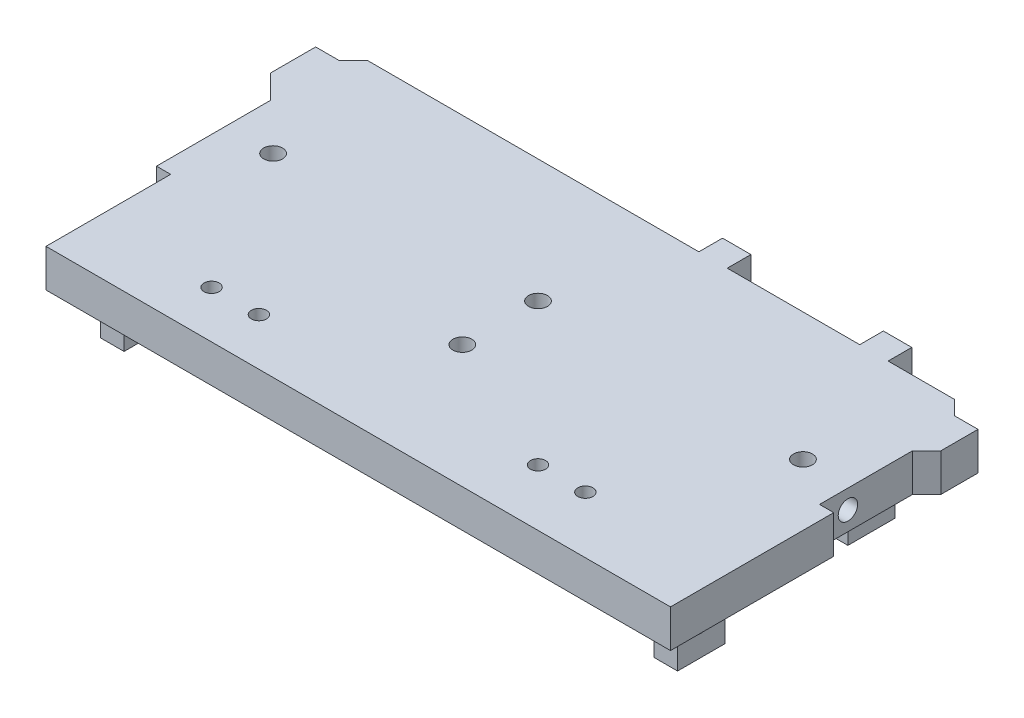
SolidWorks part; units mm, degrees
ref_plane "Alzado" through (0, 0, 0) normal (0, 0, 1) x (1, 0, 0)
ref_plane "Planta" through (0, 0, 0) normal (0, 1, 0) x (1, 0, 0)
ref_plane "Vista lateral" through (0, 0, 0) normal (1, 0, 0) x (0, 0, -1)
sketch "Croquis1" plane through (0, 0, 0) normal (0, 1, 0) x (1, 0, 0)
  line L1 (-66, -34) -> (66, -34)
  line L2 (-66, -34) -> (-66, 34)
  line L3 (-66, 34) -> (66, 34)
  line L4 (66, -34) -> (66, 34)
  line L5 (-66, -34) -> (66, 34) construction
  line L6 (-66, 34) -> (66, -34) construction
  point P0 (0, 0)
  dimension "D1" = 132
  dimension "D2" = 68
extrude "Saliente-Extruir1" add sketch "Croquis1" along normal blind 8
sketch "Croquis2" plane through (0, 8, 0) normal (0, 1, 0) x (1, 0, 0)
  line L0 (66, -34) -> (66, 0.506) construction
  line L1 (66, -34) -> (66, 34) construction
  line L2 (66, 0.506) -> (63, 0.506)
  line L3 (63, 0.506) -> (63, 20.155)
  line L4 (63, 20.155) -> (66.0003, 23.1553)
  line L5 (66.0003, 23.1553) -> (66, 0.506)
  line L6 (66.0003, 23.1553) -> (66, 31.0003)
  line L7 (66, 31.0003) -> (61, 31.0003)
  line L8 (61, 31.0003) -> (57.9997, 34.0005)
  line L9 (57.9997, 34.0005) -> (66, 34)
  line L10 (66, 34) -> (66, 31.0003)
  line M8 (66, -34) -> (66, 34)
  line M9 (66, 34) -> (-66, 34)
  dimension "D1" = 34.506
  dimension "D2" = 3
  dimension "D3" = 19.649
  dimension "D4" = 4.243
  dimension "D5" = 135
  dimension "D6" = 7.845
  dimension "D7" = 5
  dimension "D8" = 4.243
  dimension "D9" = 135
extrude "Cortar-Extruir1" cut sketch "Croquis2" against normal blind 8 contours L8 L7 M8 M9 | L5 L2 L3 L4
sketch "Croquis3" plane through (0, 8, 0) normal (0, 1, 0) x (1, 0, 0)
  line L0 (58.0003, 34) -> (44.0003, 34) construction
  line L1 (58.0003, 34) -> (-66, 34) construction
  line L2 (44.0003, 34) -> (44.0003, 39)
  line L3 (44.0003, 39) -> (38.0003, 39)
  line L4 (38.0003, 39) -> (38.0003, 34)
  line L5 (38.0003, 34) -> (44.0003, 34)
  line L6 (10.0003, 34) -> (10.0003, 39)
  line L7 (10.0003, 39) -> (4.0003, 39)
  line L8 (4.0003, 39) -> (4.0003, 34)
  line L9 (4.0003, 34) -> (10.0003, 34)
  line L10 (-66, 34) -> (-69.0003, 30.9997)
  line L11 (-69.0003, 30.9997) -> (-74.0003, 30.9997)
  line L12 (-74.0003, 30.9997) -> (-74.0003, 21.4267)
  line L13 (-74.0003, 21.4267) -> (-69.0003, 16.4268)
  line L14 (-69.0003, 16.4268) -> (-69.0003, -7.6452)
  line L15 (-69.0003, -7.6452) -> (-66, -7.6452)
  line L16 (-66, 34) -> (-66, -34) construction
  line L17 (-66, -7.6452) -> (-66, 34)
  point P10 (38.0003, 36.5)
  dimension "D1" = 14
  dimension "D2" = 5
  dimension "D3" = 6
  dimension "D4" = 6
  dimension "D5" = 28
  dimension "D6" = 4.243
  dimension "D7" = 135
  dimension "D8" = 5
  dimension "D9" = 9.573
  dimension "D10" = 7.071
  dimension "D11" = 135
  dimension "D12" = 24.072
extrude "Saliente-Extruir2" add sketch "Croquis3" against normal blind 8
sketch "Croquis4" plane through (0, 8, 0) normal (0, 1, 0) x (1, 0, 0)
  line L0 (-69.0003, 16.4268) -> (-69.0003, -7.6452) construction
  line L1 (4.0003, 34) -> (-66, 34) construction
  line L2 (-66, -7.6452) -> (-66, -34) construction
  line L3 (-66, -34) -> (66, -34) construction
  line L4 (63, 0.506) -> (63, 20.155) construction
  line L5 (58.0003, 34) -> (44.0003, 34) construction
  circle A0 centre (-59.0003, 7) radius 2
  circle A1 centre (-41, -24) radius 1.6
  circle A2 centre (-31, -24) radius 1.6
  circle A3 centre (-4.0003, 8) radius 2
  circle A4 centre (-4, -8) radius 2
  circle A5 centre (26, -22) radius 1.6
  circle A6 centre (36, -22) radius 1.6
  circle A7 centre (53, 7) radius 2
  dimension "D2" = 4
  dimension "D5" = 3.2
  dimension "D7" = 10
  dimension "D10" = 4
  dimension "D15" = 3.2
  dimension "D16" = 3.2
  dimension "D19" = 4
  dimension "D1" = 10
  dimension "D3" = 27
  dimension "D4" = 25
  dimension "D6" = 10
  dimension "D8" = 26
  dimension "D9" = 16
  dimension "D11" = 62
  dimension "D12" = 65
  dimension "D13" = 12
  dimension "D14" = 12
  dimension "D17" = 92
  dimension "D18" = 10
  dimension "D20" = 10
  dimension "D21" = 27
extrude "Cortar-Extruir2" cut sketch "Croquis4" against normal through all
sketch "Croquis5" plane through (63, 0, 0) normal (1, 0, 0) x (0, 0, -1)
  line L0 (0.506, 0) -> (0.506, 8) construction
  circle A0 centre (6.506, 4) radius 2.05
  dimension "D2" = 4.1
  dimension "D1" = 6
extrude "Cortar-Extruir3" cut sketch "Croquis5" against normal blind 6
sketch "Croquis6" plane through (0, 0, 0) normal (0, -1, 0) x (1, 0, 0)
  line L0 (4.0003, -34) -> (-66, -34) construction
  line L1 (-61.5003, -24) -> (-56.5003, -24)
  line L2 (-61.5003, -24) -> (-61.5003, -14)
  line L3 (-61.5003, -14) -> (-56.5003, -14)
  line L4 (-56.5003, -24) -> (-56.5003, -14)
  line L5 (-61.5003, -24) -> (-56.5003, -14) construction
  line L6 (-61.5003, -14) -> (-56.5003, -24) construction
  line L7 (-74.0003, -30.9997) -> (-74.0003, -21.4267) construction
  line L9 (-61.5003, 17) -> (-56.5003, 17)
  line L10 (-61.5003, 17) -> (-61.5003, 27)
  line L11 (-61.5003, 27) -> (-56.5003, 27)
  line L12 (-56.5003, 17) -> (-56.5003, 27)
  line L13 (-61.5003, 17) -> (-56.5003, 27) construction
  line L14 (-61.5003, 27) -> (-56.5003, 17) construction
  line L16 (-56.5003, 17) -> (55.4997, 17) construction
  line L17 (-56.5003, -24) -> (50.4997, -24) construction
  line L18 (55.4997, 17) -> (60.4997, 17)
  line L19 (55.4997, 17) -> (55.4997, 27)
  line L20 (55.4997, 27) -> (60.4997, 27)
  line L21 (60.4997, 17) -> (60.4997, 27)
  line L23 (50.4997, -24) -> (55.4997, -24)
  line L24 (50.4997, -24) -> (50.4997, -14)
  line L25 (50.4997, -14) -> (55.4997, -14)
  line L26 (55.4997, -24) -> (55.4997, -14)
  point P0 (-59.0003, -19)
  point P9 (-59.0003, 22)
  dimension "D1" = 5
  dimension "D2" = 10
  dimension "D3" = 10
  dimension "D4" = 12.5
  dimension "D5" = 31
  dimension "D6" = 5
  dimension "D7" = 10
  dimension "D8" = 112
  dimension "D9" = 5
  dimension "D10" = 10
  dimension "D11" = 107
  dimension "D12" = 5
  dimension "D13" = 10
extrude "Saliente-Extruir3" add sketch "Croquis6" along normal blind 10
sketch "Croquis7" plane through (55.4997, 0, 0) normal (1, 0, 0) x (0, 0, -1)
  line L0 (19, 0) -> (19, -4) construction
  line L3 (24, 0) -> (14, 0) construction
  line L4 (-22, 0) -> (-22, -4) construction
  line L5 (-17, 0) -> (-27, 0) construction
  circle A1 centre (19, -4) radius 1.55
  circle A2 centre (-22, -4) radius 1.55
  dimension "D2" = 3.1
  dimension "D1" = 4
extrude "Cortar-Extruir4" cut sketch "Croquis7" against normal through all both and the other way through all
